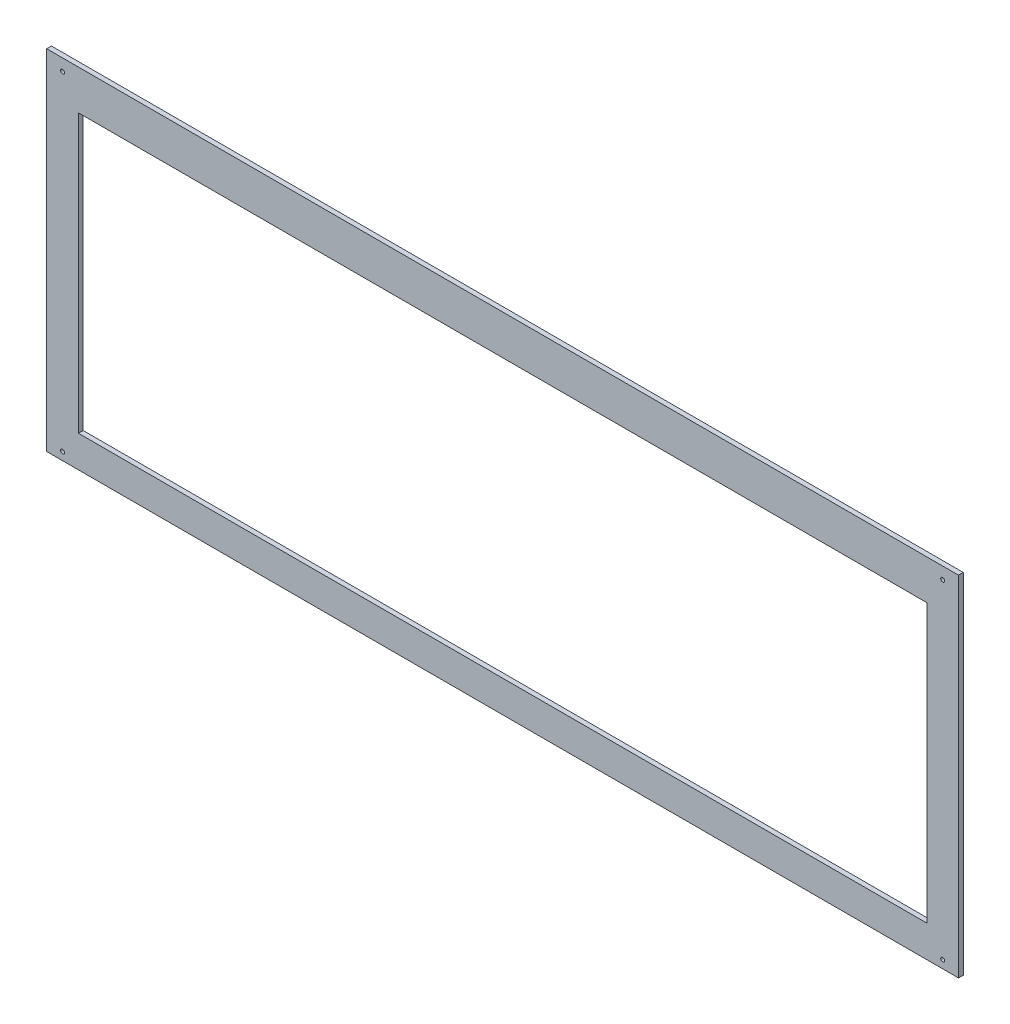
SolidWorks part; units mm, degrees
ref_plane "Front Plane" through (0, 0, 0) normal (0, 0, 1) x (1, 0, 0)
ref_plane "Top Plane" through (0, 0, 0) normal (0, 1, 0) x (1, 0, 0)
ref_plane "Right Plane" through (0, 0, 0) normal (1, 0, 0) x (0, 0, -1)
sketch "Sketch1" plane through (0, 0, 0) normal (0, 0, 1) x (1, 0, 0)
  line L0 (575, -215) -> (575, 175)
  line L1 (-535, -175) -> (535, -175)
  line L2 (-535, -175) -> (-535, 175)
  line L3 (-535, 175) -> (535, 175)
  line L4 (535, -175) -> (535, 175)
  line L5 (-535, -175) -> (535, 175) construction
  line L6 (-535, 175) -> (535, -175) construction
  line L7 (-575, -215) -> (575, -215)
  line L8 (-575, -215) -> (-575, 175)
  line L9 (-535, 225) -> (535, 225)
  line L10 (-575, 175) -> (-575, 225)
  line L11 (-575, 225) -> (-535, 225)
  line L12 (535, 225) -> (575, 225)
  line L13 (575, 225) -> (575, 175)
  point P0 (0, 0)
  dimension "D1" = 1070
  dimension "D2" = 350
  dimension "D3" = 40
  dimension "D4" = 50
extrude "Boss-Extrude1" add sketch "Sketch1" along normal blind 6
sketch "Sketch2" plane through (0, 0, 6) normal (0, 0, 1) x (1, 0, 0)
  line L0 (-575, 225) -> (-575, -215) construction
  line L1 (575, 225) -> (-575, 225) construction
  line L2 (575, -215) -> (575, 225) construction
  line L3 (-575, -215) -> (575, -215) construction
  circle A0 centre (-555, 210) radius 2.5
  circle A1 centre (-555, -205) radius 2.5
  circle A2 centre (555, -205) radius 2.5
  circle A3 centre (555, 210) radius 2.5
  dimension "D1" = 5
  dimension "D2" = 20
  dimension "D3" = 15
  dimension "D4" = 20
  dimension "D5" = 10
extrude "Cut-Extrude1" cut sketch "Sketch2" against normal through all
